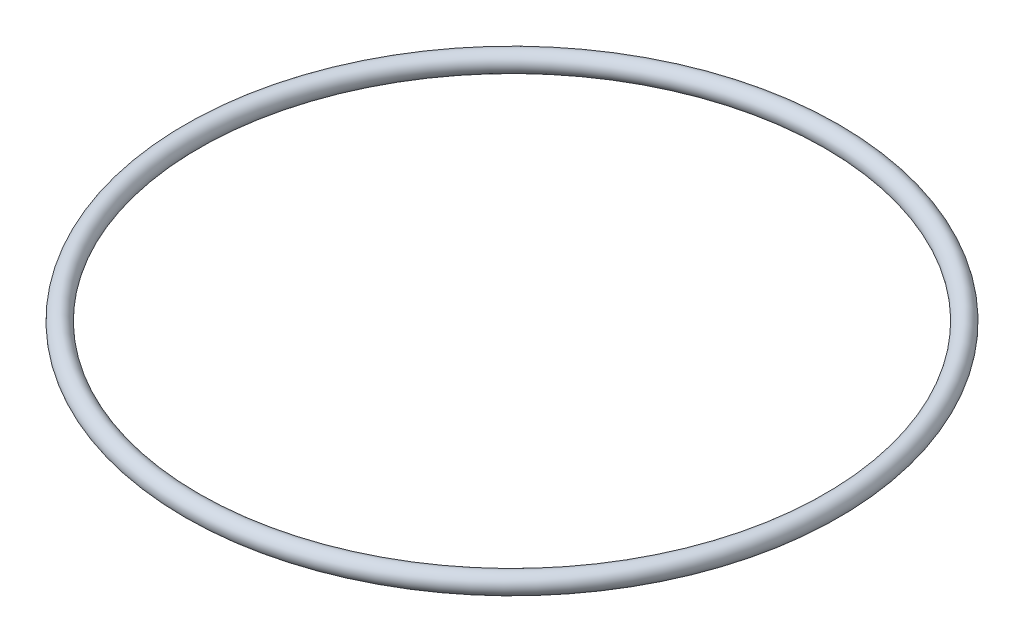
SolidWorks part; units mm, degrees
material "NBR"
ref_plane "前视基准面" through (0, 0, 0) normal (0, 0, 1) x (1, 0, 0)
ref_plane "上视基准面" through (0, 0, 0) normal (0, 1, 0) x (1, 0, 0)
ref_plane "右视基准面" through (0, 0, 0) normal (1, 0, 0) x (0, 0, -1)
other "Configuration Table"
sketch "草图1" plane through (0, 0, 0) normal (0, 1, 0) x (1, 0, 0)
  circle A0 centre (0, 0) radius 16.5
  dimension "D1" = 33
sweep "扫描1" add path "草图1" circular profile diameter 1 parameters "D3"=1
